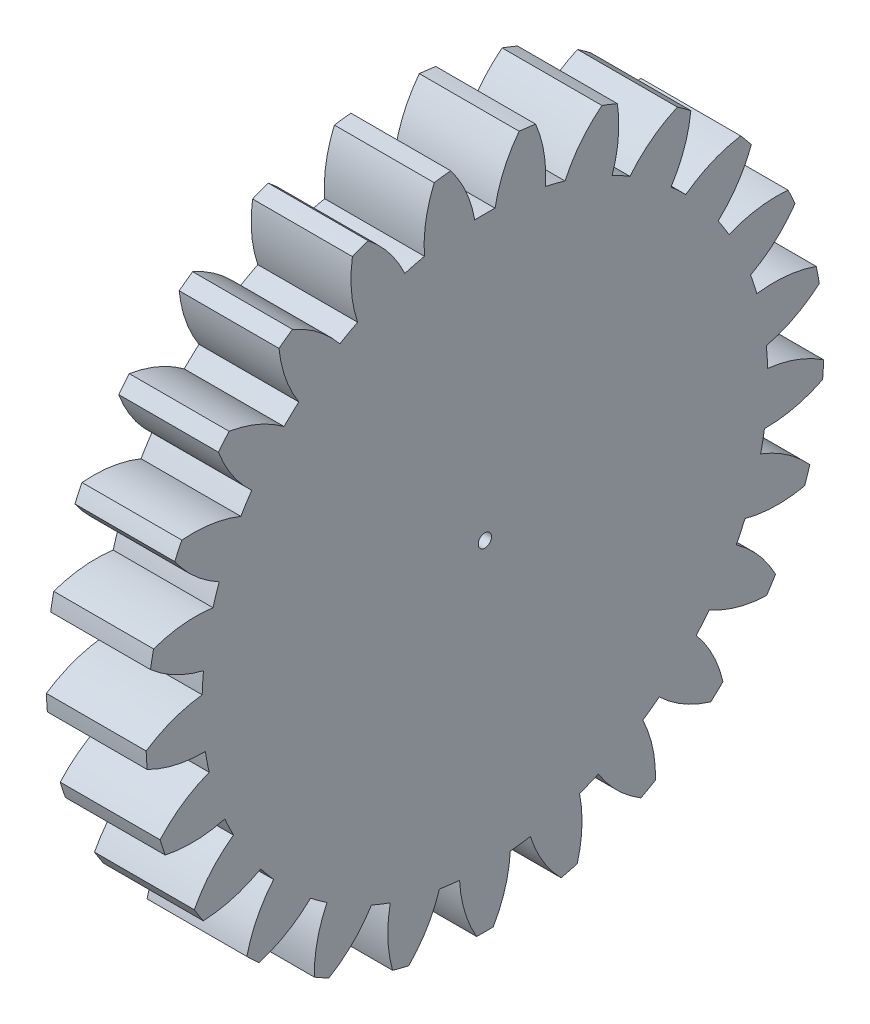
SolidWorks part; units mm, degrees
ref_plane "Plane1" through (0, 0, 0) normal (0, 0, 1) x (1, 0, 0)
ref_plane "Plane2" through (0, 0, 0) normal (0, 1, 0) x (1, 0, 0)
ref_plane "Plane3" through (0, 0, 0) normal (1, 0, 0) x (0, 0, -1)
sketch "HoldingSke" plane through (0, 0, 0) normal (0, 1, 0) x (1, 0, 0)
  line L0 (0, 0) -> (0.6042, -0.2817)
  line L1 (-15, 0) -> (100, 0) construction
  line L2 (0, 0) -> (-2.1039, 2.3779)
  line L3 (0, 0) -> (-11.863, 4.5341)
  line L4 (0, 0) -> (7.8269, 3.6497)
  line L5 (0, 0) -> (-46.8476, -17.4728)
  line L6 (0, 0) -> (-4.9738, -3.3558)
  line L7 (-2.1039, 2.3779) -> (8.6586, 51.2059)
  line L8 (-76.2, 54.61) -> (-76.1, 54.61)
  line L9 (-71.009, 38.7566) -> (-53.1078, 45.2721)
  line L10 (-76.2, 71.12) -> (104.1128, 71.12)
  line L11 (0, 0) -> (-6, 0)
  line L12 (-76.2, 101.6) -> (-76.147, 101.6)
  line L13 (24.9733, 27.94) -> (52.9518, 28.4284)
  line L14 (24.9733, 27.94) -> (24.9743, 27.94)
  line L15 (24.9733, 27.94) -> (100.4006, 29.5858)
  line L16 (-63.627, -1.5) -> (-12.827, -1.5)
  circle A0 centre (0, 0) radius 0.4
  circle A1 centre (0, 0) radius 16.874
  circle A2 centre (0, 0) radius 37.5
  circle A3 centre (0, 0) radius 0.4
  dimension "MHD" = 33.748
  dimension "Hub_dia" = 75
  dimension "Bore" = 0.8
  dimension "MBD" = 0.8
  dimension "Num_teeth" = 25
  dimension "Pitch_radius" = 180.3128
  dimension "Pitch" = 0.6667
  dimension "Width" = 6
  dimension "Overall_len" = 50
  dimension "Show_teeth" = 25
  dimension "Thickness" = 6
  dimension "OAL" = 50.0001
  dimension "T_dim" = 0.1
  dimension "Ap" = 20
  dimension "H" = 19.05
  dimension "Backlash" = 0.053
  dimension "Addendum_fac" = 1
  dimension "Dedendum_fac" = 1.25
  dimension "Clearance_fac" = 0.25
  dimension "Dedendum_add" = 0.001
  dimension "Module" = 1.5
sketch "BasProSke" plane through (0, 0, 0) normal (0, 1, 0) x (1, 0, 0)
  line L0 (-10, 0) -> (60, 0) construction
  line L1 (0, 0) -> (0, 20.25)
  line L2 (0, 0) -> (6, 0)
  line L3 (6, 0) -> (6, 20.25)
  line L4 (6, 20.25) -> (0, 20.25)
  dimension "Diameter" = 40.5
  dimension "Thickness" = 6
revolve "Base-Revolve" add sketch "BasProSke" angle 360 about L0
sketch "TooCutSke" plane through (0, 0, 0) normal (1, 0, 0) x (0, 0, -1)
  line L1 (0, 0) -> (0, 107) construction
  line L2 (0, 0) -> (-1.27, 18.7069) construction
  line L3 (0, 0) -> (-4.6921, 37.142) construction
  line L4 (-1.27, 18.7069) -> (-2.3461, 18.571) construction
  arc A0 (0.7139, 16.8589) -> (-0.7139, 16.8589) centre (0, 0) ccw
  arc A1 (2.1318, 20.163) -> (-2.1318, 20.163) centre (0, 0) ccw
  circle A2 centre (0, 0) radius 18.75 construction
  circle A3 centre (0, 0) radius 17.6192 construction
  arc A4 (-0.7139, 16.8589) -> (-2.1318, 20.163) centre (-8.1141, 15.6396) ccw
  arc A5 (2.1318, 20.163) -> (0.7139, 16.8589) centre (8.1141, 15.6396) ccw
  dimension "Root_dia" = 33.748
  dimension "Overcut_dia" = 40.5508
  dimension "Pitch_dia" = 37.5
  dimension "Base_dia" = 35.2385
  dimension "Flank_rad" = 7.5
  dimension "Half_ang" = 7.2
  dimension "Half_CT" = 1.0846
extrude "ToothCut" cut sketch "TooCutSke" along normal through all
fillet "Breaks" [suppressed] radius 0.03
fillet "RootFillets" [suppressed] radius 0.376
pattern_circular "TeethCuts" count 25 every 14.4 about axis through (-10, 0, 0) along (1, 0, 0) of "ToothCut", "RootFillets", "Breaks"
sketch "HubNeaOneSke" plane through (0, 0, 0) normal (-1, 0, 0) x (0, 0, 1)
  circle A0 centre (0, 0) radius 16.874
  dimension "Diameter" = 33.748
extrude "HubNearOne" [suppressed] add sketch "HubNeaOneSke" along normal blind 44.0001
sketch "HubNeaBotSke" plane through (0, 0, 0) normal (-1, 0, 0) x (0, 0, 1)
  circle A0 centre (0, 0) radius 16.874
  dimension "Diameter" = 33.748
extrude "HubNearBoth" [suppressed] add sketch "HubNeaBotSke" along normal blind 22
ref_plane "FarPln" through (6, 0, 0) normal (1, 0, 0) x (0, 0, -1)
sketch "HubFarSke" plane through (6, 0, 0) normal (1, 0, 0) x (0, 0, -1)
  circle A0 centre (0, 0) radius 16.874
  dimension "Diameter" = 33.748
extrude "HubFar" [suppressed] add sketch "HubFarSke" along normal blind 22
sketch "BorSke" plane through (0, 0, 0) normal (1, 0, 0) x (0, 0, -1)
  circle A0 centre (0, 0) radius 0.4
  dimension "Diameter" = 0.8
extrude "Bore" cut sketch "BorSke" along normal mid plane 100.0001
sketch "KeySke" plane through (0, 0, 0) normal (1, 0, 0) x (0, 0, -1)
  line L0 (-0.05, 0) -> (-0.05, 0.5)
  line L1 (-0.05, 0.5) -> (0.05, 0.5)
  line L2 (0.05, 0.5) -> (0.05, 0)
  line L3 (0, 0) -> (0, 34) construction
  line L4 (-0.05, 0) -> (0.05, 0)
  dimension "Offset" = 0.5
  dimension "Width" = 0.1
extrude "Keyway" [suppressed] cut sketch "KeySke" along normal mid plane 100.0001
pattern_circular "Keyway2" [suppressed] count 2 every 90 about axis through (-10, 0, 0) along (1, 0, 0)
sketch "Sketch1" plane through (6, 0, 0) normal (1, 0, 0) x (0, 0, -1)
  circle A100 centre (0, 0) radius 0.4
  circle A101 centre (0, 0) radius 0.4 construction
  arc A200 (7.0333, 19.1226) -> (4.8149, 16.3028) centre (11.7486, 13.1304) ccw
  arc A201 (4.8149, 16.3028) -> (3.6346, 16.6059) centre (0, 0) ccw
  arc A202 (3.6346, 16.6059) -> (3.049, 20.1456) centre (-3.9698, 17.1662) ccw
  arc A203 (3.049, 20.1456) -> (2.0568, 20.2709) centre (0, 0) ccw
  arc A204 (2.0568, 20.2709) -> (0.6093, 16.9881) centre (8.1141, 15.6396) ccw
  arc A205 (0.6093, 16.9881) -> (-0.6093, 16.9881) centre (0, 0) ccw
  arc A206 (-0.6093, 16.9881) -> (-2.0568, 20.2709) centre (-8.1141, 15.6396) ccw
  arc A207 (-2.0568, 20.2709) -> (-3.049, 20.1456) centre (0, 0) ccw
  arc A208 (-3.049, 20.1456) -> (-3.6346, 16.6059) centre (3.9698, 17.1662) ccw
  arc A209 (-3.6346, 16.6059) -> (-4.8149, 16.3028) centre (0, 0) ccw
  arc A210 (-4.8149, 16.3028) -> (-7.0333, 19.1226) centre (-11.7486, 13.1304) ccw
  arc A211 (-7.0333, 19.1226) -> (-7.9632, 18.7544) centre (0, 0) ccw
  arc A212 (-7.9632, 18.7544) -> (-7.6501, 15.1803) centre (-0.424, 17.6141) ccw
  arc A213 (-7.6501, 15.1803) -> (-8.718, 14.5932) centre (0, 0) ccw
  arc A214 (-8.718, 14.5932) -> (-11.5679, 16.7727) centre (-14.6449, 9.7961) ccw
  arc A215 (-11.5679, 16.7727) -> (-12.3771, 16.1848) centre (0, 0) ccw
  arc A216 (-12.3771, 16.1848) -> (-11.185, 12.8009) centre (-4.7911, 16.9553) ccw
  arc A217 (-11.185, 12.8009) -> (-12.0733, 11.9667) centre (0, 0) ccw
  arc A218 (-12.0733, 11.9667) -> (-15.3757, 13.3689) centre (-16.621, 5.8463) ccw
  arc A219 (-15.3757, 13.3689) -> (-16.0132, 12.5983) centre (0, 0) ccw
  arc A220 (-16.0132, 12.5983) -> (-14.017, 9.6171) centre (-8.8572, 15.2311) ccw
  arc A221 (-14.017, 9.6171) -> (-14.67, 8.5882) centre (0, 0) ccw
  arc A222 (-14.67, 8.5882) -> (-18.2174, 9.1251) centre (-17.5528, 1.5291) ccw
  arc A223 (-18.2174, 9.1251) -> (-18.6432, 8.2202) centre (0, 0) ccw
  arc A224 (-18.6432, 8.2202) -> (-15.9683, 5.8291) centre (-12.3668, 12.5499) ccw
  arc A225 (-15.9683, 5.8291) -> (-16.3449, 4.6701) centre (0, 0) ccw
  arc A226 (-16.3449, 4.6701) -> (-19.9144, 4.308) centre (-17.3816, -2.8841) ccw
  arc A227 (-19.9144, 4.308) -> (-20.1018, 3.3255) centre (0, 0) ccw
  arc A228 (-20.1018, 3.3255) -> (-16.9163, 1.6748) centre (-15.0993, 9.0802) ccw
  arc A229 (-16.9163, 1.6748) -> (-16.9928, 0.4586) centre (0, 0) ccw
  arc A230 (-16.9928, 0.4586) -> (-20.3601, -0.7799) centre (-16.1183, -7.1161) ccw
  arc A231 (-20.3601, -0.7799) -> (-20.2973, -1.7781) centre (0, 0) ccw
  arc A232 (-20.2973, -1.7781) -> (-16.8013, -2.5847) centre (-16.8831, 5.0398) ccw
  arc A233 (-16.8013, -2.5847) -> (-16.573, -3.7818) centre (0, 0) ccw
  arc A234 (-16.573, -3.7818) -> (-19.5265, -5.8187) centre (-13.8422, -10.901) ccw
  arc A235 (-19.5265, -5.8187) -> (-19.2174, -6.7699) centre (0, 0) ccw
  arc A236 (-19.2174, -6.7699) -> (-15.6307, -6.6818) centre (-17.606, 0.6829) ccw
  arc A237 (-15.6307, -6.6818) -> (-15.1118, -7.7845) centre (0, 0) ccw
  arc A238 (-15.1118, -7.7845) -> (-17.466, -10.492) centre (-10.6963, -14.0009) ccw
  arc A239 (-17.466, -10.492) -> (-16.93, -11.3364) centre (0, 0) ccw
  arc A240 (-16.93, -11.3364) -> (-13.4779, -10.3591) centre (-17.2227, -3.717) ccw
  arc A241 (-13.4779, -10.3591) -> (-12.7011, -11.2981) centre (0, 0) ccw
  arc A242 (-12.7011, -11.2981) -> (-14.308, -14.5059) centre (-6.8784, -16.2211) ccw
  arc A243 (-14.308, -14.5059) -> (-13.5789, -15.1906) centre (0, 0) ccw
  arc A244 (-13.5789, -15.1906) -> (-10.4783, -13.3855) centre (-15.7572, -7.8834) ccw
  arc A245 (-10.4783, -13.3855) -> (-9.4924, -14.1018) centre (0, 0) ccw
  arc A246 (-9.4924, -14.1018) -> (-10.251, -17.6085) centre (-2.6283, -17.4221) ccw
  arc A247 (-10.251, -17.6085) -> (-9.3746, -18.0903) centre (0, 0) ccw
  arc A248 (-9.3746, -18.0903) -> (-6.8203, -15.5708) centre (-13.3017, -11.5544) ccw
  arc A249 (-6.8203, -15.5708) -> (-5.6872, -16.0194) centre (0, 0) ccw
  arc A250 (-5.6872, -16.0194) -> (-5.5499, -19.6046) centre (1.787, -17.5284) ccw
  arc A251 (-5.5499, -19.6046) -> (-4.5812, -19.8533) centre (0, 0) ccw
  arc A252 (-4.5812, -19.8533) -> (-2.7337, -16.7778) centre (-10.0103, -14.4993) ccw
  arc A253 (-2.7337, -16.7778) -> (-1.5247, -16.9305) centre (0, 0) ccw
  arc A254 (-1.5247, -16.9305) -> (-0.5001, -20.3689) centre (6.09, -16.5333) ccw
  arc A255 (-0.5001, -20.3689) -> (0.5001, -20.3689) centre (0, 0) ccw
  arc A256 (0.5001, -20.3689) -> (1.5247, -16.9305) centre (-6.09, -16.5333) ccw
  arc A257 (1.5247, -16.9305) -> (2.7337, -16.7778) centre (0, 0) ccw
  arc A258 (2.7337, -16.7778) -> (4.5812, -19.8533) centre (10.0103, -14.4993) ccw
  arc A259 (4.5812, -19.8533) -> (5.5499, -19.6046) centre (0, 0) ccw
  arc A260 (5.5499, -19.6046) -> (5.6872, -16.0194) centre (-1.787, -17.5284) ccw
  arc A261 (5.6872, -16.0194) -> (6.8203, -15.5708) centre (0, 0) ccw
  arc A262 (6.8203, -15.5708) -> (9.3746, -18.0903) centre (13.3017, -11.5544) ccw
  arc A263 (9.3746, -18.0903) -> (10.251, -17.6085) centre (0, 0) ccw
  arc A264 (10.251, -17.6085) -> (9.4924, -14.1018) centre (2.6283, -17.4221) ccw
  arc A265 (9.4924, -14.1018) -> (10.4783, -13.3855) centre (0, 0) ccw
  arc A266 (10.4783, -13.3855) -> (13.5789, -15.1906) centre (15.7572, -7.8834) ccw
  arc A267 (13.5789, -15.1906) -> (14.308, -14.5059) centre (0, 0) ccw
  arc A268 (14.308, -14.5059) -> (12.7011, -11.2981) centre (6.8784, -16.2211) ccw
  arc A269 (12.7011, -11.2981) -> (13.4779, -10.3591) centre (0, 0) ccw
  arc A270 (13.4779, -10.3591) -> (16.93, -11.3364) centre (17.2227, -3.717) ccw
  arc A271 (16.93, -11.3364) -> (17.466, -10.492) centre (0, 0) ccw
  arc A272 (17.466, -10.492) -> (15.1118, -7.7845) centre (10.6963, -14.0009) ccw
  arc A273 (15.1118, -7.7845) -> (15.6307, -6.6818) centre (0, 0) ccw
  arc A274 (15.6307, -6.6818) -> (19.2174, -6.7699) centre (17.606, 0.6829) ccw
  arc A275 (19.2174, -6.7699) -> (19.5265, -5.8187) centre (0, 0) ccw
  arc A276 (19.5265, -5.8187) -> (16.573, -3.7818) centre (13.8422, -10.901) ccw
  arc A277 (16.573, -3.7818) -> (16.8013, -2.5847) centre (0, 0) ccw
  arc A278 (16.8013, -2.5847) -> (20.2973, -1.7781) centre (16.8831, 5.0398) ccw
  arc A279 (20.2973, -1.7781) -> (20.3601, -0.7799) centre (0, 0) ccw
  arc A280 (20.3601, -0.7799) -> (16.9928, 0.4586) centre (16.1183, -7.1161) ccw
  arc A281 (16.9928, 0.4586) -> (16.9163, 1.6748) centre (0, 0) ccw
  arc A282 (16.9163, 1.6748) -> (20.1018, 3.3255) centre (15.0993, 9.0802) ccw
  arc A283 (20.1018, 3.3255) -> (19.9144, 4.308) centre (0, 0) ccw
  arc A284 (19.9144, 4.308) -> (16.3449, 4.6701) centre (17.3816, -2.8841) ccw
  arc A285 (16.3449, 4.6701) -> (15.9683, 5.8291) centre (0, 0) ccw
  arc A286 (15.9683, 5.8291) -> (18.6432, 8.2202) centre (12.3668, 12.5499) ccw
  arc A287 (18.6432, 8.2202) -> (18.2174, 9.1251) centre (0, 0) ccw
  arc A288 (18.2174, 9.1251) -> (14.67, 8.5882) centre (17.5528, 1.5291) ccw
  arc A289 (14.67, 8.5882) -> (14.017, 9.6171) centre (0, 0) ccw
  arc A290 (14.017, 9.6171) -> (16.0132, 12.5983) centre (8.8572, 15.2311) ccw
  arc A291 (16.0132, 12.5983) -> (15.3757, 13.3689) centre (0, 0) ccw
  arc A292 (15.3757, 13.3689) -> (12.0733, 11.9667) centre (16.621, 5.8463) ccw
  arc A293 (12.0733, 11.9667) -> (11.185, 12.8009) centre (0, 0) ccw
  arc A294 (11.185, 12.8009) -> (12.3771, 16.1848) centre (4.7911, 16.9553) ccw
  arc A295 (12.3771, 16.1848) -> (11.5679, 16.7727) centre (0, 0) ccw
  arc A296 (11.5679, 16.7727) -> (8.718, 14.5932) centre (14.6449, 9.7961) ccw
  arc A297 (8.718, 14.5932) -> (7.6501, 15.1803) centre (0, 0) ccw
  arc A298 (7.6501, 15.1803) -> (7.9632, 18.7544) centre (0.424, 17.6141) ccw
  arc A299 (7.9632, 18.7544) -> (7.0333, 19.1226) centre (0, 0) ccw
  arc A300 (7.0333, 19.1226) -> (4.8149, 16.3028) centre (11.7486, 13.1304) ccw
  arc A301 (4.8149, 16.3028) -> (3.6346, 16.6059) centre (0, 0) ccw
  arc A302 (3.6346, 16.6059) -> (3.049, 20.1456) centre (-3.9698, 17.1662) ccw
  arc A303 (3.049, 20.1456) -> (2.0568, 20.2709) centre (0, 0) ccw
  arc A304 (2.0568, 20.2709) -> (0.6093, 16.9881) centre (8.1141, 15.6396) ccw
  arc A305 (0.6093, 16.9881) -> (-0.6093, 16.9881) centre (0, 0) ccw
  arc A306 (-0.6093, 16.9881) -> (-2.0568, 20.2709) centre (-8.1141, 15.6396) ccw
  arc A307 (-2.0568, 20.2709) -> (-3.049, 20.1456) centre (0, 0) ccw
  arc A308 (-3.049, 20.1456) -> (-3.6346, 16.6059) centre (3.9698, 17.1662) ccw
  arc A309 (-3.6346, 16.6059) -> (-4.8149, 16.3028) centre (0, 0) ccw
  arc A310 (-4.8149, 16.3028) -> (-7.0333, 19.1226) centre (-11.7486, 13.1304) ccw
  arc A311 (-7.0333, 19.1226) -> (-7.9632, 18.7544) centre (0, 0) ccw
  arc A312 (-7.9632, 18.7544) -> (-7.6501, 15.1803) centre (-0.424, 17.6141) ccw
  arc A313 (-7.6501, 15.1803) -> (-8.718, 14.5932) centre (0, 0) ccw
  arc A314 (-8.718, 14.5932) -> (-11.5679, 16.7727) centre (-14.6449, 9.7961) ccw
  arc A315 (-11.5679, 16.7727) -> (-12.3771, 16.1848) centre (0, 0) ccw
  arc A316 (-12.3771, 16.1848) -> (-11.185, 12.8009) centre (-4.7911, 16.9553) ccw
  arc A317 (-11.185, 12.8009) -> (-12.0733, 11.9667) centre (0, 0) ccw
  arc A318 (-12.0733, 11.9667) -> (-15.3757, 13.3689) centre (-16.621, 5.8463) ccw
  arc A319 (-15.3757, 13.3689) -> (-16.0132, 12.5983) centre (0, 0) ccw
  arc A320 (-16.0132, 12.5983) -> (-14.017, 9.6171) centre (-8.8572, 15.2311) ccw
  arc A321 (-14.017, 9.6171) -> (-14.67, 8.5882) centre (0, 0) ccw
  arc A322 (-14.67, 8.5882) -> (-18.2174, 9.1251) centre (-17.5528, 1.5291) ccw
  arc A323 (-18.2174, 9.1251) -> (-18.6432, 8.2202) centre (0, 0) ccw
  arc A324 (-18.6432, 8.2202) -> (-15.9683, 5.8291) centre (-12.3668, 12.5499) ccw
  arc A325 (-15.9683, 5.8291) -> (-16.3449, 4.6701) centre (0, 0) ccw
  arc A326 (-16.3449, 4.6701) -> (-19.9144, 4.308) centre (-17.3816, -2.8841) ccw
  arc A327 (-19.9144, 4.308) -> (-20.1018, 3.3255) centre (0, 0) ccw
  arc A328 (-20.1018, 3.3255) -> (-16.9163, 1.6748) centre (-15.0993, 9.0802) ccw
  arc A329 (-16.9163, 1.6748) -> (-16.9928, 0.4586) centre (0, 0) ccw
  arc A330 (-16.9928, 0.4586) -> (-20.3601, -0.7799) centre (-16.1183, -7.1161) ccw
  arc A331 (-20.3601, -0.7799) -> (-20.2973, -1.7781) centre (0, 0) ccw
  arc A332 (-20.2973, -1.7781) -> (-16.8013, -2.5847) centre (-16.8831, 5.0398) ccw
  arc A333 (-16.8013, -2.5847) -> (-16.573, -3.7818) centre (0, 0) ccw
  arc A334 (-16.573, -3.7818) -> (-19.5265, -5.8187) centre (-13.8422, -10.901) ccw
  arc A335 (-19.5265, -5.8187) -> (-19.2174, -6.7699) centre (0, 0) ccw
  arc A336 (-19.2174, -6.7699) -> (-15.6307, -6.6818) centre (-17.606, 0.6829) ccw
  arc A337 (-15.6307, -6.6818) -> (-15.1118, -7.7845) centre (0, 0) ccw
  arc A338 (-15.1118, -7.7845) -> (-17.466, -10.492) centre (-10.6963, -14.0009) ccw
  arc A339 (-17.466, -10.492) -> (-16.93, -11.3364) centre (0, 0) ccw
  arc A340 (-16.93, -11.3364) -> (-13.4779, -10.3591) centre (-17.2227, -3.717) ccw
  arc A341 (-13.4779, -10.3591) -> (-12.7011, -11.2981) centre (0, 0) ccw
  arc A342 (-12.7011, -11.2981) -> (-14.308, -14.5059) centre (-6.8784, -16.2211) ccw
  arc A343 (-14.308, -14.5059) -> (-13.5789, -15.1906) centre (0, 0) ccw
  arc A344 (-13.5789, -15.1906) -> (-10.4783, -13.3855) centre (-15.7572, -7.8834) ccw
  arc A345 (-10.4783, -13.3855) -> (-9.4924, -14.1018) centre (0, 0) ccw
  arc A346 (-9.4924, -14.1018) -> (-10.251, -17.6085) centre (-2.6283, -17.4221) ccw
  arc A347 (-10.251, -17.6085) -> (-9.3746, -18.0903) centre (0, 0) ccw
  arc A348 (-9.3746, -18.0903) -> (-6.8203, -15.5708) centre (-13.3017, -11.5544) ccw
  arc A349 (-6.8203, -15.5708) -> (-5.6872, -16.0194) centre (0, 0) ccw
  arc A350 (-5.6872, -16.0194) -> (-5.5499, -19.6046) centre (1.787, -17.5284) ccw
  arc A351 (-5.5499, -19.6046) -> (-4.5812, -19.8533) centre (0, 0) ccw
  arc A352 (-4.5812, -19.8533) -> (-2.7337, -16.7778) centre (-10.0103, -14.4993) ccw
  arc A353 (-2.7337, -16.7778) -> (-1.5247, -16.9305) centre (0, 0) ccw
  arc A354 (-1.5247, -16.9305) -> (-0.5001, -20.3689) centre (6.09, -16.5333) ccw
  arc A355 (-0.5001, -20.3689) -> (0.5001, -20.3689) centre (0, 0) ccw
  arc A356 (0.5001, -20.3689) -> (1.5247, -16.9305) centre (-6.09, -16.5333) ccw
  arc A357 (1.5247, -16.9305) -> (2.7337, -16.7778) centre (0, 0) ccw
  arc A358 (2.7337, -16.7778) -> (4.5812, -19.8533) centre (10.0103, -14.4993) ccw
  arc A359 (4.5812, -19.8533) -> (5.5499, -19.6046) centre (0, 0) ccw
  arc A360 (5.5499, -19.6046) -> (5.6872, -16.0194) centre (-1.787, -17.5284) ccw
  arc A361 (5.6872, -16.0194) -> (6.8203, -15.5708) centre (0, 0) ccw
  arc A362 (6.8203, -15.5708) -> (9.3746, -18.0903) centre (13.3017, -11.5544) ccw
  arc A363 (9.3746, -18.0903) -> (10.251, -17.6085) centre (0, 0) ccw
  arc A364 (10.251, -17.6085) -> (9.4924, -14.1018) centre (2.6283, -17.4221) ccw
  arc A365 (9.4924, -14.1018) -> (10.4783, -13.3855) centre (0, 0) ccw
  arc A366 (10.4783, -13.3855) -> (13.5789, -15.1906) centre (15.7572, -7.8834) ccw
  arc A367 (13.5789, -15.1906) -> (14.308, -14.5059) centre (0, 0) ccw
  arc A368 (14.308, -14.5059) -> (12.7011, -11.2981) centre (6.8784, -16.2211) ccw
  arc A369 (12.7011, -11.2981) -> (13.4779, -10.3591) centre (0, 0) ccw
  arc A370 (13.4779, -10.3591) -> (16.93, -11.3364) centre (17.2227, -3.717) ccw
  arc A371 (16.93, -11.3364) -> (17.466, -10.492) centre (0, 0) ccw
  arc A372 (17.466, -10.492) -> (15.1118, -7.7845) centre (10.6963, -14.0009) ccw
  arc A373 (15.1118, -7.7845) -> (15.6307, -6.6818) centre (0, 0) ccw
  arc A374 (15.6307, -6.6818) -> (19.2174, -6.7699) centre (17.606, 0.6829) ccw
  arc A375 (19.2174, -6.7699) -> (19.5265, -5.8187) centre (0, 0) ccw
  arc A376 (19.5265, -5.8187) -> (16.573, -3.7818) centre (13.8422, -10.901) ccw
  arc A377 (16.573, -3.7818) -> (16.8013, -2.5847) centre (0, 0) ccw
  arc A378 (16.8013, -2.5847) -> (20.2973, -1.7781) centre (16.8831, 5.0398) ccw
  arc A379 (20.2973, -1.7781) -> (20.3601, -0.7799) centre (0, 0) ccw
  arc A380 (20.3601, -0.7799) -> (16.9928, 0.4586) centre (16.1183, -7.1161) ccw
  arc A381 (16.9928, 0.4586) -> (16.9163, 1.6748) centre (0, 0) ccw
  arc A382 (16.9163, 1.6748) -> (20.1018, 3.3255) centre (15.0993, 9.0802) ccw
  arc A383 (20.1018, 3.3255) -> (19.9144, 4.308) centre (0, 0) ccw
  arc A384 (19.9144, 4.308) -> (16.3449, 4.6701) centre (17.3816, -2.8841) ccw
  arc A385 (16.3449, 4.6701) -> (15.9683, 5.8291) centre (0, 0) ccw
  arc A386 (15.9683, 5.8291) -> (18.6432, 8.2202) centre (12.3668, 12.5499) ccw
  arc A387 (18.6432, 8.2202) -> (18.2174, 9.1251) centre (0, 0) ccw
  arc A388 (18.2174, 9.1251) -> (14.67, 8.5882) centre (17.5528, 1.5291) ccw
  arc A389 (14.67, 8.5882) -> (14.017, 9.6171) centre (0, 0) ccw
  arc A390 (14.017, 9.6171) -> (16.0132, 12.5983) centre (8.8572, 15.2311) ccw
  arc A391 (16.0132, 12.5983) -> (15.3757, 13.3689) centre (0, 0) ccw
  arc A392 (15.3757, 13.3689) -> (12.0733, 11.9667) centre (16.621, 5.8463) ccw
  arc A393 (12.0733, 11.9667) -> (11.185, 12.8009) centre (0, 0) ccw
  arc A394 (11.185, 12.8009) -> (12.3771, 16.1848) centre (4.7911, 16.9553) ccw
  arc A395 (12.3771, 16.1848) -> (11.5679, 16.7727) centre (0, 0) ccw
  arc A396 (11.5679, 16.7727) -> (8.718, 14.5932) centre (14.6449, 9.7961) ccw
  arc A397 (8.718, 14.5932) -> (7.6501, 15.1803) centre (0, 0) ccw
  arc A398 (7.6501, 15.1803) -> (7.9632, 18.7544) centre (0.424, 17.6141) ccw
  arc A399 (7.9632, 18.7544) -> (7.0333, 19.1226) centre (0, 0) ccw
  dimension "D1" = 0.125
extrude "Boss-Extrude1" add sketch "Sketch1" against normal up to surface (6 mm away) up to face at (0, 0, 0)
equation "' \"Module@HoldingSke\" = 6.35"
equation "' \"Num_teeth@HoldingSke\" = 12"
equation "' \"Ap@HoldingSke\" =  20"
equation "' \"Width@HoldingSke\" = 0.5 * 25.4"
equation "' \"Hub_dia@HoldingSke\"= 1 * 25.4"
equation "' \"Overall_len@HoldingSke\" = 1.0 * 25.4"
equation "' \"Bore@HoldingSke\" = 0.75 * 25.4"
equation "' \"T_dim@HoldingSke\" = 0.1 * 25.4"
equation "' \"Width@KeySke\" = 0.25 * 25.4"
equation "' \"Show_teeth@HoldingSke\" = 13"
equation "' \"Backlash@HoldingSke\" = 0.009 * 25.4"
equation "' \"Addendum_fac@HoldingSke\" = 1.0"
equation "' \"Dedendum_fac@HoldingSke\" = 1.25"
equation "' \"Dedendum_add@HoldingSke\" = 0.00005 * 25.4"
equation "' \"Clearance_fac@HoldingSke\" = 0.25"
equation "\"Pitch@HoldingSke\" = 1 / \"Module@HoldingSke\""
equation "\"Overcut_dia@TooCutSke\" = (\"Num_teeth@HoldingSke\" + 2 * \"Addendum_fac@HoldingSke\") / \"Pitch@HoldingSke\" + 0.002 * 25.4"
equation "\"Pitch_dia@TooCutSke\" = \"Num_teeth@HoldingSke\" / \"Pitch@HoldingSke\""
equation "\"Base_dia@TooCutSke\" = \"Num_teeth@HoldingSke\" / \"Pitch@HoldingSke\" * cos((\"Ap@HoldingSke\"  * 3.14159265 / 180))"
equation "\"Root_dia@TooCutSke\" = (\"Num_teeth@HoldingSke\" + 2) / \"Pitch@HoldingSke\" - 2 * (\"Addendum_fac@HoldingSke\" + \"Dedendum_fac@HoldingSke\") / \"Pitch@HoldingSke\" - \"Dedendum_add@HoldingSke\" * 2"
equation "\"Half_ang@TooCutSke\" = 180 / \"Num_teeth@HoldingSke\""
equation "\"Half_CT@TooCutSke\" = \"Num_teeth@HoldingSke\" / \"Pitch@HoldingSke\" * sin((3.14159265 / 2 / \"Num_teeth@HoldingSke\")) / 2 - 7 * \"Backlash@HoldingSke\" / 4"
equation "\"Flank_rad@TooCutSke\" = \"Num_teeth@HoldingSke\" / \"Pitch@HoldingSke\" / 5"
equation "\"Radius@RootFillets\" = \"Clearance_fac@HoldingSke\" / \"Pitch@HoldingSke\" + \"Dedendum_add@HoldingSke\""
equation "\"Break_rad@Breaks\" = 0.02 / \"Pitch@HoldingSke\""
equation "\"Thickness@HoldingSke\" = \"Width@HoldingSke\""
equation "\"OAL@HoldingSke\" = \"Thickness@HoldingSke\""
equation "\"MHD@HoldingSke\" = (\"Num_teeth@HoldingSke\" + 2) / \"Pitch@HoldingSke\" - 2 * (\"Addendum_fac@HoldingSke\" + \"Dedendum_fac@HoldingSke\")  / \"Pitch@HoldingSke\" - \"Dedendum_add@HoldingSke\" * 2"
equation "\"MBD@HoldingSke\" = (\"Num_teeth@HoldingSke\" + 2) / \"Pitch@HoldingSke\" - 2 * (\"Addendum_fac@HoldingSke\" + \"Dedendum_fac@HoldingSke\")  / \"Pitch@HoldingSke\" - \"Dedendum_add@HoldingSke\" * 2 - 0.002 * 25.4"
equation "\"MHD@HoldingSke\" = ((sgn( \"MHD@HoldingSke\" - \"Hub_dia@HoldingSke\" )-1)*( \"MHD@HoldingSke\" - \"Hub_dia@HoldingSke\" ))/-2+ \"Hub_dia@HoldingSke\""
equation "\"MBD@HoldingSke\" = ((sgn( \"MBD@HoldingSke\" - \"Bore@HoldingSke\" )-1)*( \"MBD@HoldingSke\" - \"Bore@HoldingSke\" ))/-2+ \"Bore@HoldingSke\""
equation "\"OAL@HoldingSke\" = ((sgn( \"OAL@HoldingSke\" - \"Overall_len@HoldingSke\" )+1)*( \"OAL@HoldingSke\" - \"Overall_len@HoldingSke\" ))/2 + \"Overall_len@HoldingSke\" + 0.000002 * 25.4"
equation "\"Num_teeth@TeethCuts\" = int( \"Show_teeth@HoldingSke\" ) + 1"
equation "\"Num_teeth@TeethCuts\" = ((sgn( \"Num_teeth@TeethCuts\" - \"Num_teeth@HoldingSke\" )-1)*( \"Num_teeth@TeethCuts\" - \"Num_teeth@HoldingSke\" ))/-2+ \"Num_teeth@HoldingSke\""
equation "\"Num_teeth@TeethCuts\" = ((sgn( \"Num_teeth@TeethCuts\" - 2.0)+1)*( \"Num_teeth@TeethCuts\" - 2.0))/2 +2.0"
equation "\"Angle@TeethCuts\" = 360.0 / \"Num_teeth@HoldingSke\""
equation "\"Diameter@BasProSke\" = (\"Num_teeth@HoldingSke\" + 2 * \"Addendum_fac@HoldingSke\") / \"Pitch@HoldingSke\""
equation "\"Thickness@BasProSke\"  = \"Thickness@HoldingSke\""
equation "' \"Fillet_rad@BasProSke\" =  \"Thickness@HoldingSke\" * 0.05"
equation "\"MHD@HoldingSke\" = ((sgn( \"MHD@HoldingSke\" - \"Root_dia@TooCutSke\" )-1)*( \"MHD@HoldingSke\" - \"Root_dia@TooCutSke\" ))/-2+ \"Root_dia@TooCutSke\""
equation "\"Diameter@HubNeaOneSke\" = \"MHD@HoldingSke\""
equation "\"Length@HubNearOne\" = \"OAL@HoldingSke\" - \"Thickness@BasProSke\""
equation "\"Diameter@HubNeaBotSke\" = \"MHD@HoldingSke\""
equation "\"Length@HubNearBoth\" = ( \"OAL@HoldingSke\" - \"Thickness@BasProSke\" ) / 2.0"
equation "\"Thickness@FarPln\" = \"Thickness@BasProSke\""
equation "\"Diameter@HubFarSke\" = \"MHD@HoldingSke\""
equation "\"Length@HubFar\" = ( \"OAL@HoldingSke\" - \"Thickness@BasProSke\" ) / 2.0"
equation "\"Diameter@BorSke\" = \"MBD@HoldingSke\""
equation "\"D1@Bore\" = \"OAL@HoldingSke\" * 2.0"
equation "\"D1@Keyway\" = \"OAL@HoldingSke\" * 2.0"
equation "\"Offset@KeySke\" = \"T_dim@HoldingSke\" + \"MBD@HoldingSke\" / 2.0"
